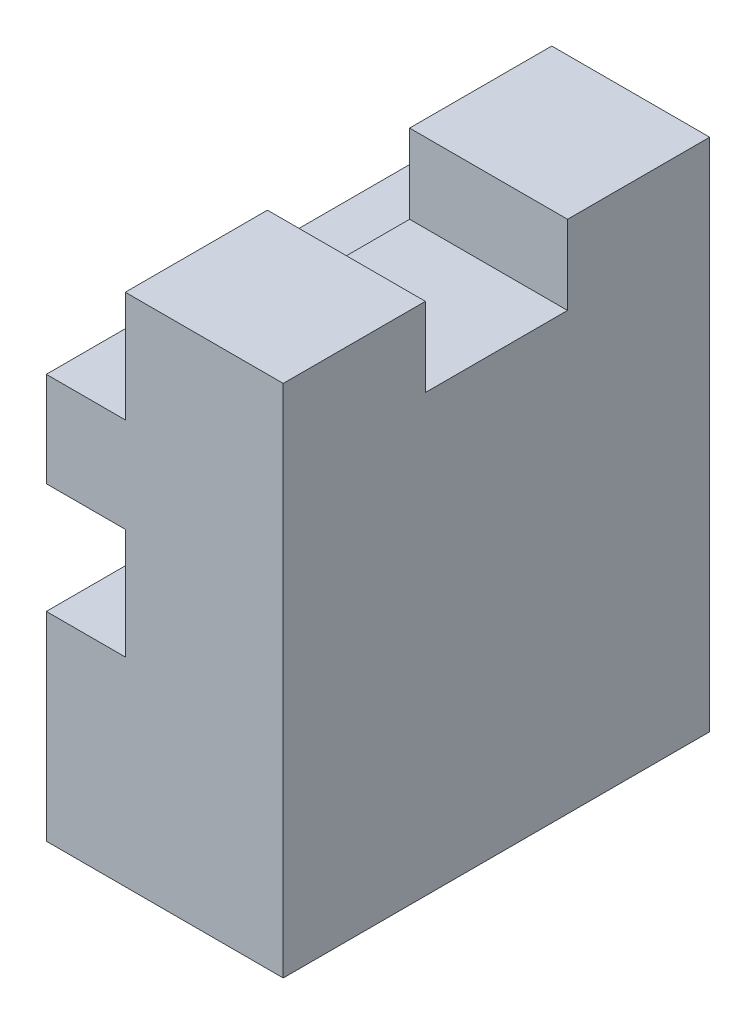
SolidWorks part; units mm, degrees
ref_plane "前视基准面" through (0, 0, 0) normal (0, 0, 1) x (1, 0, 0)
ref_plane "上视基准面" through (0, 0, 0) normal (0, 1, 0) x (1, 0, 0)
ref_plane "右视基准面" through (0, 0, 0) normal (1, 0, 0) x (0, 0, -1)
other "Configuration Table"
sketch "草图1" plane through (0, 0, 0) normal (0, 0, 1) x (1, 0, 0)
  line L0 (0, 0) -> (10, 0)
  line L8 (10, -32.6) -> (-5, -32.6)
  line L9 (-5, -32.6) -> (-5, -20)
  line L10 (-5, -20) -> (0, -20)
  line L11 (0, -20) -> (0, -13)
  line L12 (0, -13) -> (-5, -13)
  line L13 (-5, -13) -> (-5, -7)
  line L14 (-5, -7) -> (0, -7)
  line L15 (0, -7) -> (0, 0)
  line L16 (10, 0) -> (10, -32.6)
  dimension "D3" = 6
  dimension "D4" = 7
  dimension "D5" = 5
  dimension "D6" = 7
  dimension "D7" = 12.6
  dimension "D8" = 10
extrude "凸台-拉伸1" add sketch "草图1" along normal blind 27
sketch "草图2" plane through (0, 0, 0) normal (0, 1, 0) x (1, 0, 0)
  line L0 (0, -27) -> (0, 0) construction
  line L1 (0, -9) -> (10, -9)
  line L2 (0, -9) -> (0, -18)
  line L3 (0, -18) -> (10, -18)
  line L4 (10, -9) -> (10, -18)
  line L5 (10, -27) -> (10, 0) construction
  line L6 (10, 0) -> (0, 0) construction
  line L7 (10, -27) -> (0, -27) construction
  dimension "D1" = 9
  dimension "D2" = 9
extrude "切除-拉伸1" cut sketch "草图2" against normal blind 5
